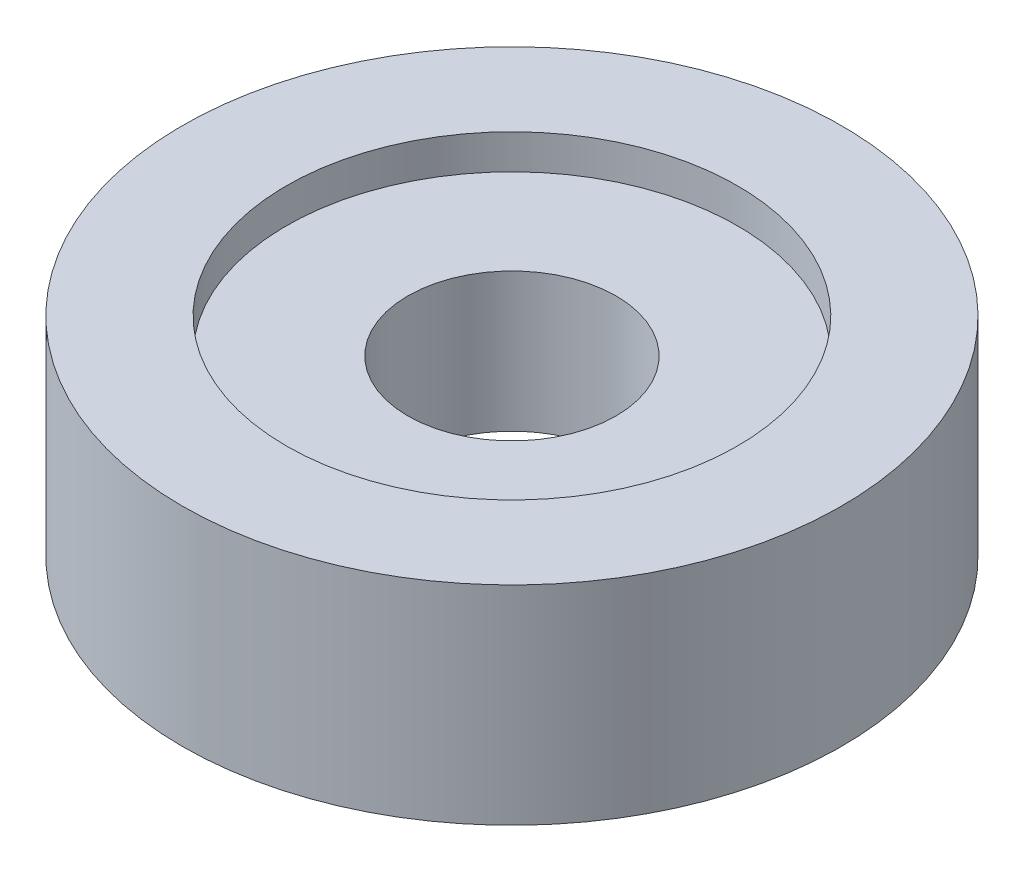
SolidWorks part; units mm, degrees
ref_plane "Front Plane" through (0, 0, 0) normal (0, 0, 1) x (1, 0, 0)
ref_plane "Top Plane" through (0, 0, 0) normal (0, 1, 0) x (1, 0, 0)
ref_plane "Right Plane" through (0, 0, 0) normal (1, 0, 0) x (0, 0, -1)
sketch "Sketch1" plane through (0, 0, 0) normal (0, 1, 0) x (1, 0, 0)
  circle A0 centre (0, 0) radius 9.5
  dimension "D1" = 19
extrude "Boss-Extrude1" add sketch "Sketch1" along normal blind 6
sketch "Sketch2" plane through (0, 6, 0) normal (0, 1, 0) x (1, 0, 0)
  circle A0 centre (0, 0) radius 9.5 construction
  circle A1 centre (0, 0) radius 9.5
  circle A2 centre (0, 0) radius 6.5
  dimension "D1" = 3
extrude "Cut-Extrude1" cut sketch "Sketch2" against normal blind 1 contours A2
sketch "Sketch3" plane through (0, 5, 0) normal (0, 1, 0) x (1, 0, 0)
  circle A0 centre (0, 0) radius 6.5 construction
  circle A1 centre (0, 0) radius 6.5
  circle A2 centre (0, 0) radius 3
  dimension "D1" = 3.5
extrude "Cut-Extrude2" cut sketch "Sketch3" against normal through all contours A2
ref_plane "Plane1" through (0, 3, 0) normal (0, 1, 0) x (1, 0, 0)
mirror "Mirror1" about plane through (0, 3, 0) normal (0, 1, 0) of "Cut-Extrude1"
